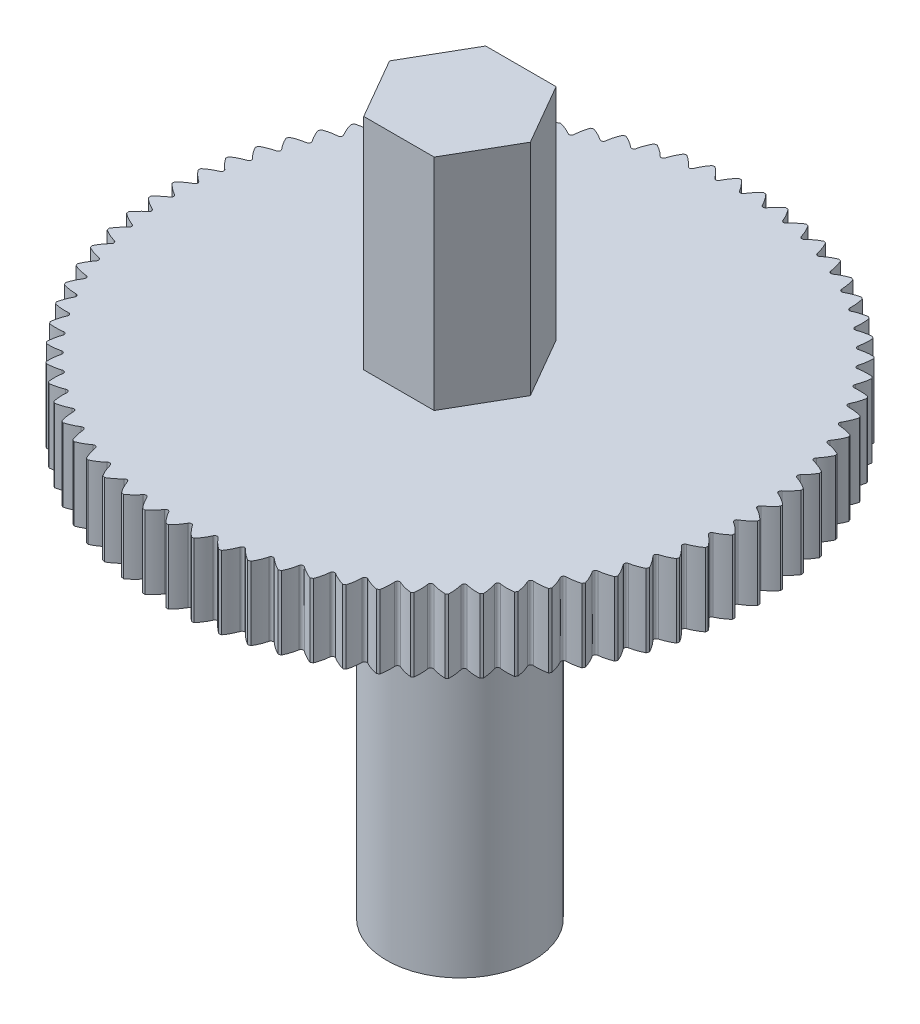
SolidWorks part; units mm, degrees
ref_plane "Front Plane" through (0, 0, 0) normal (0, 0, 1) x (1, 0, 0)
ref_plane "Top Plane" through (0, 0, 0) normal (0, 1, 0) x (1, 0, 0)
ref_plane "Right Plane" through (0, 0, 0) normal (1, 0, 0) x (0, 0, -1)
sketch "Sketch1" plane through (0, 0, 0) normal (0, 0, 1) x (1, 0, 0)
  line L0 (0, 0) -> (0, 29)
  line L1 (0, 29) -> (3, 29)
  line L2 (3, 29) -> (3, 20)
  line L3 (3, 20) -> (12, 20)
  line L4 (12, 20) -> (12, 17)
  line L5 (12, 17) -> (3, 17)
  line L6 (3, 17) -> (3, 0)
  line L7 (3, 0) -> (0, 0)
  dimension "D1" = 29
  dimension "D2" = 3
  dimension "D3" = 3
  dimension "D4" = 9
  dimension "D5" = 17
  dimension "D6" = 3
revolve "Revolve1" add sketch "Sketch1" angle 360 about L0
sketch "Sketch2" plane through (0, 20, 0) normal (0, 1, 0) x (1, 0, 0)
  line L0 (0, 0) -> (0, 12) construction
  line L1 (-0.4601, 12.0007) -> (0.4601, 12.0007)
  circle A0 centre (0, 0) radius 12 construction
  arc A1 (0.4601, 12.0007) -> (0.0901, 11.5566) centre (1.7955, 10.5119) ccw
  arc A2 (0.0901, 11.5566) -> (-0.0947, 11.5679) centre (0, 11.6) cw
  arc A4 (-0.4601, 12.0007) -> (-0.0901, 11.5566) centre (-1.7955, 10.5119) cw
  dimension "D3" = 2
extrude "Cut-Extrude2" cut sketch "Sketch2" against normal blind 10
pattern_circular "CirPattern1" count 75 over 360 about axis through (0, 0, 0) along (0, 1, 0) of "Cut-Extrude2"
sketch "Sketch3" plane through (0, 29, 0) normal (0, 1, 0) x (1, 0, 0)
  line L1 (2.8868, 0) -> (1.4434, 2.5)
  line L2 (1.4434, 2.5) -> (-1.4434, 2.5)
  line L3 (-1.4434, 2.5) -> (-2.8868, 0)
  line L4 (-2.8868, 0) -> (-1.4434, -2.5)
  line L5 (-1.4434, -2.5) -> (1.4434, -2.5)
  line L6 (1.4434, -2.5) -> (2.8868, 0)
  circle A0 centre (0, 0) radius 2.5 construction
  circle A2 centre (0, 0) radius 3 construction
  circle A3 centre (0, 0) radius 3
  dimension "D1" = 5
extrude "Cut-Extrude3" cut sketch "Sketch3" against normal blind 9
